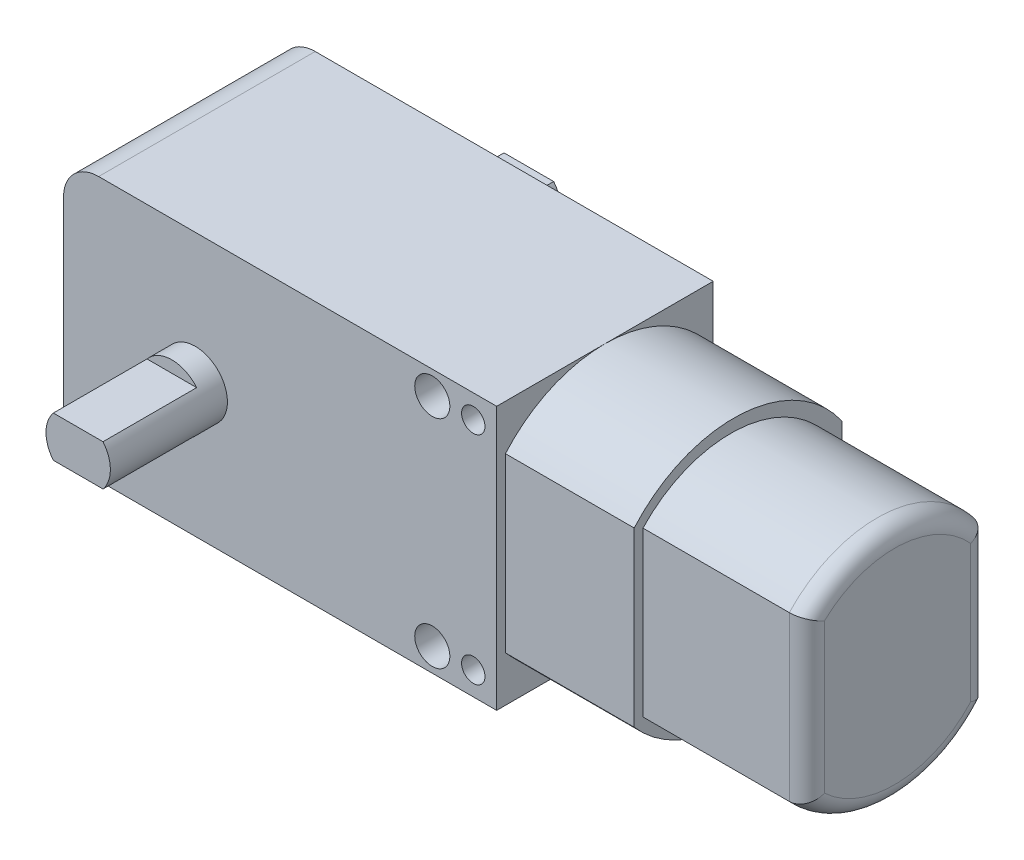
SolidWorks part; units mm, degrees
ref_plane "Face" through (0, 0, 0) normal (0, 0, 1) x (1, 0, 0)
ref_plane "Dessus" through (0, 0, 0) normal (0, 1, 0) x (1, 0, 0)
ref_plane "Droite" through (0, 0, 0) normal (1, 0, 0) x (0, 0, -1)
sketch "Esquisse1" plane through (0, 0, 0) normal (0, 0, 1) x (1, 0, 0)
  line L1 (3, 0) -> (37, 0)
  line L2 (0, 3) -> (0, 19.5)
  line L3 (3, 22.5) -> (37, 22.5)
  line L4 (37, 0) -> (37, 22.5)
  arc A0 (3, 22.5) -> (0, 19.5) centre (3, 19.5) ccw
  arc A1 (3, 0) -> (0, 3) centre (3, 3) cw
  point P6 (0, 22.5)
  point P9 (0, 0)
  dimension "D3" = 3
  dimension "D4" = 3
  dimension "D1" = 37
  dimension "D2" = 22.5
extrude "Бобышка 1" add sketch "Esquisse1" against normal blind 18.5
sketch "Esquisse2" plane through (37, 0, 0) normal (1, 0, 0) x (0, 0, -1)
  line L0 (18.5, 0) -> (0, 22.5) construction
  line L1 (0, 0) -> (18.5, 22.5) construction
  circle A0 centre (9.25, 11.25) radius 11.25
  dimension "D1" = 22.5
extrude "Бобышка 2" add sketch "Esquisse2" along normal blind 11
sketch "Esquisse3" plane through (48, 0, 0) normal (1, 0, 0) x (0, 0, -1)
  line L1 (-6.5136, -0.2934) -> (0.75, -0.2934)
  line L2 (-6.5136, -0.2934) -> (-6.5136, 22.7066)
  line L3 (-6.5136, 22.7066) -> (0.75, 22.7066)
  line L4 (0.75, -0.2934) -> (0.75, 22.7066)
  circle A0 centre (9.25, 11.25) radius 11.25 construction
  dimension "D1" = 23
  dimension "D2" = 8.5
extrude "Вырез 1" cut sketch "Esquisse3" against normal blind 11
sketch "Esquisse4" plane through (48, 0, 0) normal (1, 0, 0) x (0, 0, -1)
  line L1 (18.5, 0) -> (21.7506, 0)
  line L2 (18.5, 0) -> (18.5, 22.4202)
  line L3 (18.5, 22.4202) -> (21.7506, 22.4202)
  line L4 (21.7506, 0) -> (21.7506, 22.4202)
extrude "Вырез 2" cut sketch "Esquisse4" against normal blind 11
sketch "Esquisse5" plane through (48, 0, 0) normal (1, 0, 0) x (0, 0, -1)
  line L0 (1.5, 18.2366) -> (1.5, 4.2634)
  line L1 (17, 4.842) -> (17, 17.658)
  arc A0 (17, 17.658) -> (1.5, 18.2366) centre (9, 11.25) ccw
  arc A1 (1.5, 4.2634) -> (17, 4.842) centre (9, 11.25) ccw
extrude "Бобышка 3" add sketch "Esquisse5" along normal blind 14
fillet "Скругление" radius 1.5 4 edges at (62, 11.25, -17) (62, 1.0071, -9.3824) (62, 11.25, -1.5) (62, 21.4929, -9.3824)
sketch "Esquisse6" plane through (0, 0, -18.5) normal (0, 0, -1) x (-1, 0, 0)
  line L0 (-11.25, 28.6769) -> (-11.25, -6.0456) construction
  line L1 (0, 19.5) -> (0, 3) construction
  line L2 (-0.1502, 11.25) -> (-60.0776, 11.25) construction
  line L3 (-48, 11.25) -> (-37, 11.25) construction
  circle A0 centre (-11.25, 11.3156) radius 2.75
  dimension "D2" = 5.5
  dimension "D1" = 11.25
extrude "Рычаг" add sketch "Esquisse6" along normal blind 10
sketch "Esquisse7" plane through (0, 0, -28.5) normal (0, 0, -1) x (-1, 0, 0)
  line L1 (-14.4729, 15.1043) -> (-7.9492, 15.1043)
  line L2 (-14.4729, 15.1043) -> (-14.4729, 13.0656)
  line L3 (-14.4729, 13.0656) -> (-7.9492, 13.0656)
  line L4 (-7.9492, 15.1043) -> (-7.9492, 13.0656)
  line L5 (-14.4729, 9.5656) -> (-7.2487, 9.5656)
  line L6 (-14.4729, 9.5656) -> (-14.4729, 7.8996)
  line L7 (-14.4729, 7.8996) -> (-7.2487, 7.8996)
  line L8 (-7.2487, 9.5656) -> (-7.2487, 7.8996)
  circle A0 centre (-11.25, 11.3156) radius 2.75 construction
  dimension "D2" = 1.75
  dimension "D1" = 3.5
extrude "Вырез" cut sketch "Esquisse7" against normal blind 8
ref_plane "Plan1" through (0, 0, -9.25) normal (0, 0, -1) x (-1, 0, 0)
mirror "Отражение" about plane through (0, 0, -9.25) normal (0, 0, -1) of "Рычаг", "Вырез"
sketch "Esquisse8" plane through (0, 0, 0) normal (-1, 0, 0) x (0, 0, 1)
  line L0 (-9.25, 12.375) -> (-9.25, -12.375) construction
  line L1 (-10.75, 14) -> (-7.75, 14)
  line L2 (-10.75, 14) -> (-10.75, 9)
  line L3 (-10.75, 9) -> (-7.75, 9)
  line L4 (-7.75, 14) -> (-7.75, 9)
  line L5 (-18.5, 22.5) -> (0, 22.5) construction
  dimension "D1" = 5
  dimension "D2" = 3
  dimension "D3" = 1.5
  dimension "D4" = 8.5
extrude "Бобышка" add sketch "Esquisse8" along normal blind 4.5
sketch "Esquisse9" plane through (0, 0, -7.75) normal (0, 0, 1) x (1, 0, 0)
  line L0 (0, 14) -> (-4.5, 9) construction
  line L1 (-4.5, 14) -> (0, 9) construction
  circle A0 centre (-2.25, 11.5) radius 1
  dimension "D1" = 2
extrude "Вырез 4" cut sketch "Esquisse9" against normal up to next
sketch "Esquisse10" plane through (0, 0, -18.5) normal (0, 0, -1) x (-1, 0, 0)
  line L0 (-31.5, 30.5049) -> (-31.5, -7.7233) construction
  line L1 (-70.6391, 20.5) -> (4.1277, 20.5) construction
  line L2 (0, 19.5) -> (0, 3) construction
  line L3 (-37, 22.5) -> (-3, 22.5) construction
  line L4 (-69.4423, 2) -> (7.6478, 2) construction
  line L5 (-3, 0) -> (-37, 0) construction
  line L6 (-35, 26.4216) -> (-35, -8.1457) construction
  circle A0 centre (-31.5, 20.5) radius 1.5
  circle A1 centre (-31.5, 2) radius 1.5
  circle A2 centre (-35, 20.5) radius 1
  circle A3 centre (-35, 2) radius 1
  dimension "D4" = 3
  dimension "D5" = 3
  dimension "D7" = 2
  dimension "D8" = 2
  dimension "D1" = 31.5
  dimension "D2" = 2
  dimension "D3" = 2
  dimension "D6" = 3.5
extrude "Вырез 5" cut sketch "Esquisse10" against normal up to surface (18.5 mm away) up to face at (14, 11.3156, 0)
sketch "Esquisse11" plane through (0, 0, -18.5) normal (0, 0, -1) x (-1, 0, 0)
  line L0 (-22, 28.4537) -> (-22, -5.8225) construction
  line L1 (0, 19.5) -> (0, 3) construction
  line L2 (-4.4613, 11.3156) -> (-30.158, 11.3156) construction
  circle A0 centre (-22, 11.3156) radius 2
  dimension "D2" = 4
  dimension "D1" = 22
extrude "Бобышка 4" add sketch "Esquisse11" along normal blind 2
fillet "Скругление 2" radius 0.2 1 edges at (20, 11.3156, -20.5)
sketch "Sketch1" plane through (0, 0, -18.5) normal (0, 0, -1) x (-1, 0, 0)
  line L0 (0, 11.25) -> (-62, 11.25) construction
  line L1 (0, 19.5) -> (0, 3) construction
  line L2 (-62, 5.3923) -> (-62, 17.1077) construction
  circle A3 centre (-35, 20.5) radius 1 construction
  circle A4 centre (-31.5, 20.5) radius 1.5 construction
  circle A5 centre (-35, 20.5) radius 1
  circle A6 centre (-31.5, 20.5) radius 1.5
  point P6 (-11.25, 11.3156)
  point P7 (-22, 11.3156)
  dimension "D2" = 31.5
  dimension "D5" = 3
  dimension "D4" = 9.1844
